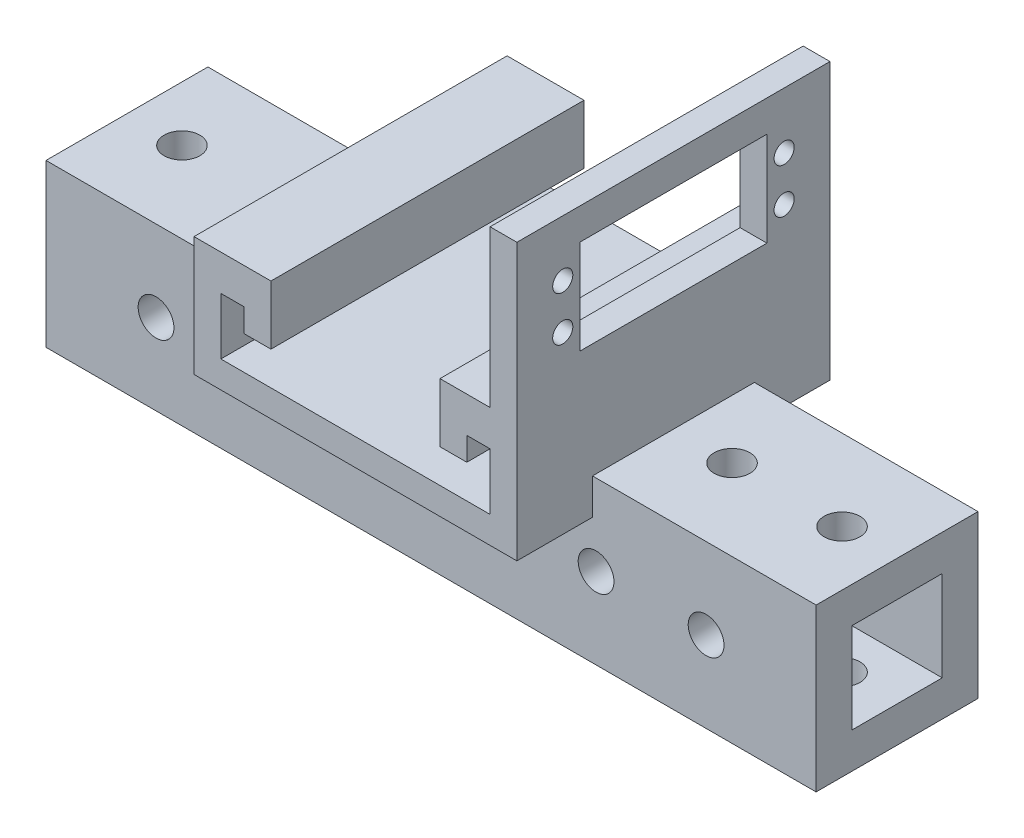
SolidWorks part; units mm, degrees
material "Nylon 101"
ref_plane "Front Plane" through (0, 0, 0) normal (0, 0, 1) x (1, 0, 0)
ref_plane "Top Plane" through (0, 0, 0) normal (0, 1, 0) x (1, 0, 0)
ref_plane "Right Plane" through (0, 0, 0) normal (1, 0, 0) x (0, 0, -1)
sketch "Sketch1" plane through (0, 0, 0) normal (0, 0, 1) x (1, 0, 0)
  line L0 (0, 26.7) -> (0, 0)
  line L1 (0, 0) -> (72.2, 0)
  line L2 (72.2, 0) -> (72.2, 61.7)
  line L3 (72.2, 61.7) -> (66.2, 61.7)
  line L4 (66.2, 61.7) -> (66.2, 26.7)
  line L5 (66.2, 6) -> (6, 6)
  line L6 (6, 6) -> (6, 18.7)
  line L7 (6, 18.7) -> (11.2, 18.7)
  line L8 (0, 26.7) -> (17.2, 26.7)
  line L10 (11.2, 18.7) -> (11.2, 13.5)
  line L11 (11.2, 13.5) -> (17.2, 13.5)
  line L12 (17.2, 13.5) -> (17.2, 26.7)
  line L13 (66.2, 26.7) -> (55, 26.7)
  line L14 (55, 26.7) -> (55, 13.5)
  line L15 (55, 13.5) -> (61, 13.5)
  line L16 (61, 13.5) -> (61, 18.7)
  line L17 (61, 18.7) -> (66.2, 18.7)
  line L18 (66.2, 18.7) -> (66.2, 6)
  dimension "D1" = 8
  dimension "D2" = 6
  dimension "D3" = 6
  dimension "D4" = 5.2
  dimension "D5" = 12.7
  dimension "D6" = 6
  dimension "D7" = 5.2
  dimension "D8" = 5.2
  dimension "D9" = 6
  dimension "D10" = 60.2
  dimension "D11" = 6
  dimension "D12" = 35
extrude "Boss-Extrude1" add sketch "Sketch1" along normal blind 70
sketch "Sketch2" plane through (66.2, 0, 0) normal (-1, 0, 0) x (0, 0, 1)
  line L0 (2.7925, 49.13) -> (69.059, 49.13) construction
  line L1 (-6.5011, 39.13) -> (69.3462, 39.13) construction
  line L2 (35, 71.9535) -> (35, 13.091) construction
  line L3 (14.1, 54.68) -> (55.9, 54.68)
  line L4 (14.1, 54.68) -> (14.1, 33.58)
  line L5 (14.1, 33.58) -> (55.9, 33.58)
  line L6 (55.9, 54.68) -> (55.9, 33.58)
  line L7 (10.25, 67.6327) -> (10.25, 27.1576) construction
  line L8 (59.75, 65.3819) -> (59.75, 32.7492) construction
  circle A0 centre (10.25, 49.13) radius 2.25
  circle A1 centre (10.25, 39.13) radius 2.25
  circle A2 centre (59.75, 49.13) radius 2.25
  circle A3 centre (59.75, 39.13) radius 2.25
  dimension "D3" = 41.8
  dimension "D2" = 5.55
  dimension "D7" = 4.5
  dimension "D8" = 4.5
  dimension "D9" = 4.5
  dimension "D10" = 4.5
  dimension "D1" = 33.58
  dimension "D4" = 21.1
  dimension "D5" = 5.55
  dimension "D6" = 14.1
  dimension "D11" = 20.9
  dimension "D12" = 49.5
  dimension "D13" = 24.75
extrude "Cut-Extrude1" cut sketch "Sketch2" against normal blind 6
sketch "Sketch3" plane through (0, 18.7, 0) normal (0, -1, 0) x (1, 0, 0)
  line L0 (61.1, 56) -> (66.1, 56)
  line L2 (0, 70) -> (72.2, 70) construction
  line L4 (61, 70) -> (61, 0) construction
  arc A0 (66.1, 56) -> (61.1, 56) centre (63.6, 56) ccw
  dimension "D1" = 5
  dimension "D2" = 14
  dimension "D3" = 2.6
revolve "Cut-Revolve1" cut sketch "Sketch3" angle 360 about L0
pattern_linear "LPattern1" count 4 spacing 14 along (0, 0, -1) count 2 spacing 55 along (-1, 0, 0) of "Cut-Revolve1"
sketch "Sketch4" plane through (72.2, 0, 0) normal (1, 0, 0) x (0, 0, -1)
  line L0 (-70, 0) -> (-70, 61.7) construction
  line L1 (-53.1, 8) -> (-16.9, 8)
  line L2 (-53.1, 8) -> (-53.1, 0)
  line L3 (-53.1, 0) -> (-16.9, 0)
  line L4 (-16.9, 8) -> (-16.9, 0)
  line L5 (-53.1, 8) -> (-16.9, 0) construction
  line L6 (-53.1, 0) -> (-16.9, 8) construction
  line L7 (-70, 0) -> (0, 0) construction
  point P0 (-35, 4)
  dimension "D1" = 8
  dimension "D2" = 36.2
  dimension "D3" = 16.9
extrude "Boss-Extrude2" add sketch "Sketch4" along normal blind 50
sketch "Sketch5" plane through (0, 0, 0) normal (-1, 0, 0) x (0, 0, 1)
  line L0 (70, 0) -> (0, 0) construction
  line L1 (16.9, 8) -> (53.1, 8)
  line L2 (16.9, 8) -> (16.9, 0)
  line L3 (16.9, 0) -> (53.1, 0)
  line L4 (53.1, 8) -> (53.1, 0)
  line L5 (16.9, 8) -> (53.1, 0) construction
  line L6 (16.9, 0) -> (53.1, 8) construction
  point P0 (35, 4)
  dimension "D1" = 36.2
  dimension "D2" = 8
  dimension "D3" = 16.9
extrude "Boss-Extrude3" add sketch "Sketch5" along normal blind 50
sketch "Sketch6" plane through (0, 0, 0) normal (0, -1, 0) x (1, 0, 0)
  line L1 (-50, 53.1) -> (122.2, 53.1)
  line L2 (-50, 53.1) -> (-50, 45.1)
  line L3 (-50, 45.1) -> (122.2, 45.1)
  line L4 (122.2, 53.1) -> (122.2, 45.1)
  line L5 (-50, 53.1) -> (122.2, 45.1) construction
  line L6 (-50, 45.1) -> (122.2, 53.1) construction
  line L8 (36.1, 88.6654) -> (36.1, -15.4325) construction
  line L10 (-50, 16.9) -> (122.2, 16.9)
  line L11 (-50, 16.9) -> (-50, 24.9)
  line L12 (-50, 24.9) -> (122.2, 24.9)
  line L13 (122.2, 16.9) -> (122.2, 24.9)
  line L14 (-50, 16.9) -> (122.2, 24.9) construction
  line L15 (-50, 24.9) -> (122.2, 16.9) construction
  point P0 (36.1, 49.1)
  point P11 (36.1, 20.9)
  dimension "D1" = 8
  dimension "D2" = 20.2
  dimension "D3" = 16.9
  dimension "D4" = 36.2
  dimension "D5" = 172.2
  dimension "D6" = 36.1
extrude "Boss-Extrude4" add sketch "Sketch6" along normal blind 20.2
sketch "Sketch7" plane through (0, -20.2, 0) normal (0, -1, 0) x (1, 0, 0)
  line L0 (122.2, 53.1) -> (-50, 53.1) construction
  line L1 (-50, 53.1) -> (122.2, 53.1)
  line L2 (-50, 53.1) -> (-50, 16.9)
  line L3 (-50, 16.9) -> (122.2, 16.9)
  line L4 (122.2, 53.1) -> (122.2, 16.9)
  line L5 (-50, 53.1) -> (122.2, 16.9) construction
  line L6 (-50, 16.9) -> (122.2, 53.1) construction
  line L7 (-50, 16.9) -> (122.2, 16.9) construction
  line L8 (-50, 53.1) -> (-50, 45.1) construction
  line L9 (122.2, 16.9) -> (122.2, 24.9) construction
  point P0 (36.1, 35)
extrude "Boss-Extrude5" add sketch "Sketch7" along normal blind 8
sketch "Sketch8" plane through (0, 0, 53.1) normal (0, 0, 1) x (1, 0, 0)
  line L0 (-77.4342, -10.1) -> (140.6874, -10.1) construction
  line L1 (-50, -28.2) -> (-50, 8) construction
  circle A0 centre (-25.4, -10.1) radius 4
  dimension "D3" = 8
  dimension "D1" = 10.1
  dimension "D2" = 24.6
extrude "Cut-Extrude2" cut sketch "Sketch8" against normal through all
pattern_linear "LPattern2" count 6 spacing 24.6 along (1, 0, 0) of "Cut-Extrude2"
sketch "Sketch9" plane through (0, 8, 0) normal (0, 1, 0) x (1, 0, 0)
  line L0 (-50, -16.9) -> (0, -16.9) construction
  line L2 (-50, -53.1) -> (-50, -16.9) construction
  circle A0 centre (-37.7, -35) radius 4
  circle A1 centre (-13.1, -35) radius 4
  dimension "D5" = 8
  dimension "D6" = 8
  dimension "D1" = 18.1
  dimension "D2" = 18.1
  dimension "D3" = 24.6
  dimension "D4" = 12.3
extrude "Cut-Extrude3" cut sketch "Sketch9" against normal through all
ref_plane "Plane1" through (36.1, 0, 0) normal (-1, 0, 0) x (0, 0, 1)
mirror "Mirror1" about plane through (36.1, 0, 0) normal (-1, 0, 0) of "Cut-Extrude3"
